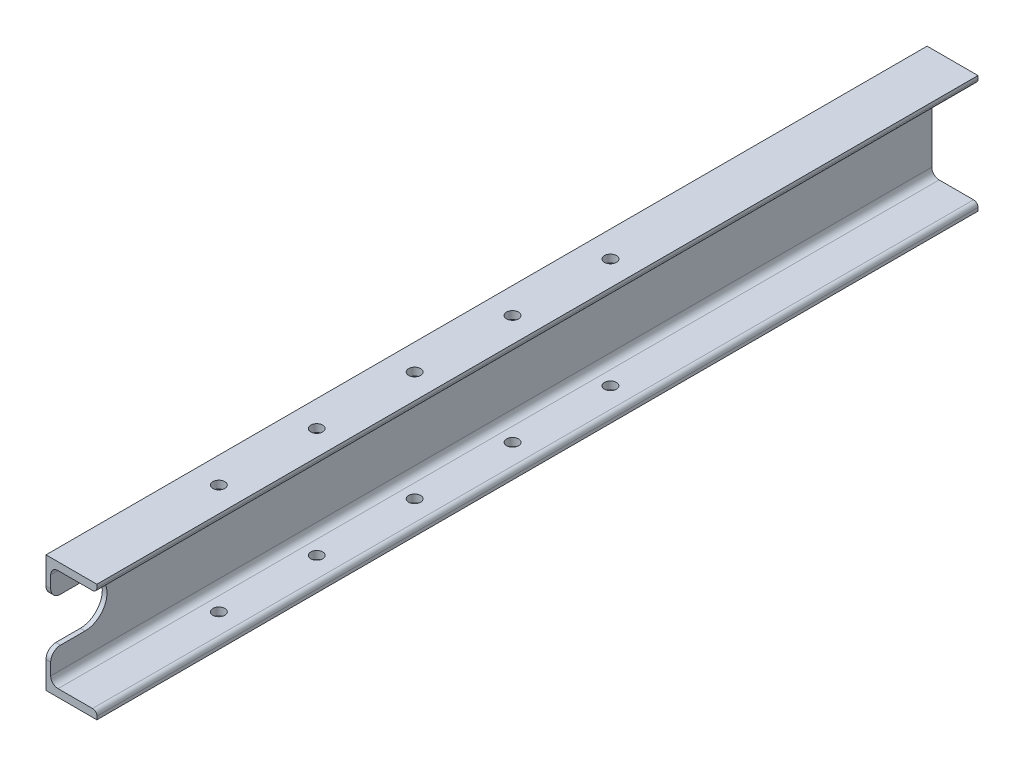
SolidWorks part; units mm, degrees
material "Сталь 3 ГОСТ 535-88"
ref_plane "Спереди" through (0, 0, 0) normal (0, 0, 1) x (1, 0, 0)
ref_plane "Сверху" through (0, 0, 0) normal (0, 1, 0) x (1, 0, 0)
ref_plane "Справа" through (0, 0, 0) normal (1, 0, 0) x (0, 0, -1)
sketch "Эскиз1" plane through (0, 0, 0) normal (0, 0, 1) x (1, 0, 0)
  line L0 (0, -60) -> (0, 60)
  line L1 (0, 60) -> (52, 60)
  line L2 (52, 60) -> (52, 56.7)
  line L3 (47.5, 52.2) -> (12.3, 52.2)
  line L4 (4.8, 44.7) -> (4.8, -44.7)
  line L5 (55, 0) -> (-55, 0) construction
  line L6 (47.5, -52.2) -> (12.3, -52.2)
  line L7 (52, -60) -> (52, -56.7)
  line L8 (0, -60) -> (52, -60)
  arc A0 (52, 56.7) -> (47.5, 52.2) centre (47.5, 56.7) cw
  arc A1 (47.5, -52.2) -> (52, -56.7) centre (47.5, -56.7) cw
  arc A2 (12.3, 52.2) -> (4.8, 44.7) centre (12.3, 44.7) ccw
  arc A3 (12.3, -52.2) -> (4.8, -44.7) centre (12.3, -44.7) cw
  point P10 (0, 0)
  point P11 (4.8, 0)
  point P15 (52, 52.2)
  point P18 (52, -52.2)
  point P21 (4.8, 52.2)
  point P24 (4.8, -52.2)
  dimension "D5" = 4.5
  dimension "D6" = 7.5
  dimension "D1" = 120
  dimension "D2" = 52
  dimension "D3" = 4.8
  dimension "D4" = 7.8
extrude "Бобышка-Вытянуть1" add sketch "Эскиз1" along normal mid plane 900
sketch "Эскиз2" plane through (0, 0, 0) normal (-1, 0, 0) x (0, 0, 1)
  line L0 (450, 0) -> (415, 0) construction
  line L2 (450, 60) -> (450, -60) construction
  line L3 (415, 22.5) -> (450, 22.5)
  line L4 (450, 22.5) -> (450, -22.5)
  line L5 (450, -22.5) -> (415, -22.5)
  arc A0 (415, 22.5) -> (415, -22.5) centre (415, 0) ccw
  dimension "D1" = 45
  dimension "D2" = 35
extrude "Вырез-Вытянуть1" cut sketch "Эскиз2" against normal mid plane 10
fillet "Скругление1" radius 10 2 edges at (2.4, -22.5, 450) (2.4, 22.5, 450)
sketch "Эскиз3" plane through (0, 60, 0) normal (0, 1, 0) x (1, 0, 0)
  line L0 (26.5508, -300) -> (26, -450) construction
  line L1 (52, -450) -> (0, -450) construction
  line L2 (26.5508, -300) -> (52, -300) construction
  line L3 (52, -450) -> (52, 450) construction
  circle A0 centre (26.5508, -300) radius 6.1
  circle A1 centre (26.5508, -200) radius 6.1
  circle A2 centre (26.5508, -100) radius 6.1
  circle A3 centre (26.5508, 0) radius 6.1
  circle A4 centre (26.5508, 100) radius 6.1
  dimension "D1" = 12.2
  dimension "D3" = 100
  dimension "D4" = 150
  dimension "D5" = 25.4492
  dimension "D2" = 5
extrude "Вырез-Вытянуть2" cut sketch "Эскиз3" against normal through all both and the other way through all
